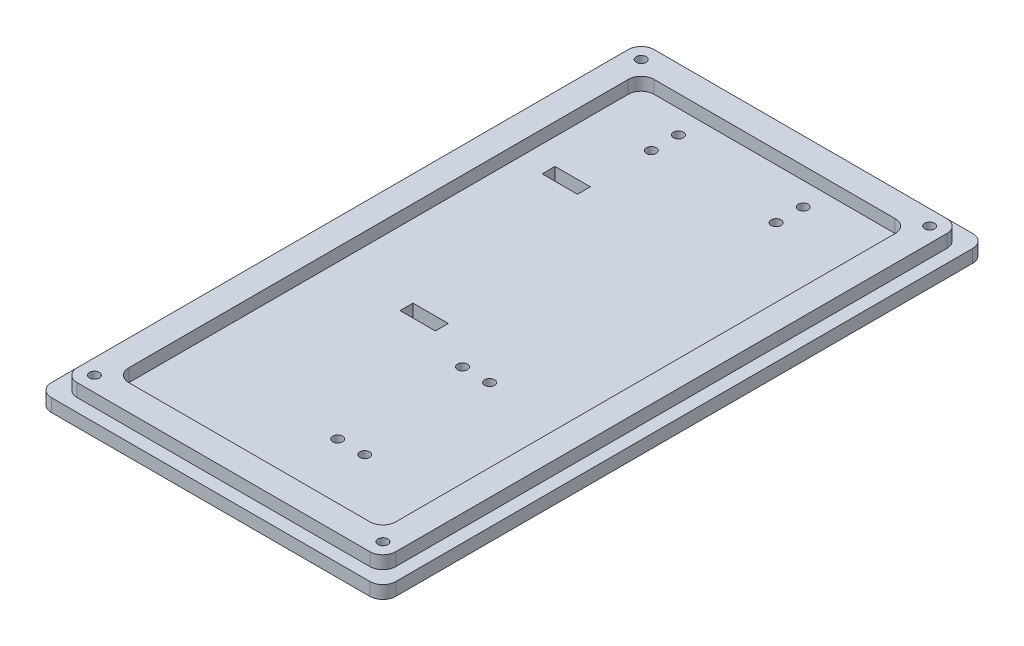
SolidWorks part; units mm, degrees
material "ABS"
ref_plane "Front Plane" through (0, 0, 0) normal (0, 0, 1) x (1, 0, 0)
ref_plane "Top Plane" through (0, 0, 0) normal (0, 1, 0) x (1, 0, 0)
ref_plane "Right Plane" through (0, 0, 0) normal (1, 0, 0) x (0, 0, -1)
sketch "Sketch1" plane through (0, 0, 0) normal (0, 1, 0) x (1, 0, 0)
  line L1 (3, 0) -> (77, 0)
  line L2 (0, 3) -> (0, 137)
  line L3 (3, 140) -> (77, 140)
  line L4 (80, 3) -> (80, 137)
  arc A0 (77, 0) -> (80, 3) centre (77, 3) ccw
  arc A1 (3, 0) -> (0, 3) centre (3, 3) cw
  arc A2 (77, 140) -> (80, 137) centre (77, 137) cw
  arc A3 (0, 137) -> (3, 140) centre (3, 137) cw
  point P9 (0, 0)
  point P12 (80, 140)
  point P15 (0, 140)
  dimension "D3" = 3
  dimension "D1" = 80
  dimension "D2" = 140
extrude "Boss-Extrude1" add sketch "Sketch1" along normal blind 3
sketch "Sketch2" plane through (0, 3, 0) normal (0, 1, 0) x (1, 0, 0)
  line L0 (0, 137) -> (0, 3) construction
  line L1 (6, 137) -> (74, 137)
  line L2 (3, 134) -> (3, 6)
  line L3 (6, 3) -> (74, 3)
  line L4 (77, 134) -> (77, 6)
  line L5 (77, 140) -> (3, 140) construction
  line L6 (80, 3) -> (80, 137) construction
  line L7 (3, 0) -> (77, 0) construction
  line L9 (12, 131) -> (68, 131)
  line L10 (9, 128) -> (9, 12)
  line L11 (12, 9) -> (68, 9)
  line L12 (71, 128) -> (71, 12)
  arc A0 (74, 137) -> (77, 134) centre (74, 134) cw
  arc A1 (74, 3) -> (77, 6) centre (74, 6) ccw
  arc A2 (3, 6) -> (6, 3) centre (6, 6) ccw
  arc A3 (6, 137) -> (3, 134) centre (6, 134) ccw
  arc A4 (9, 12) -> (12, 9) centre (12, 12) ccw
  arc A5 (68, 9) -> (71, 12) centre (68, 12) ccw
  arc A6 (68, 131) -> (71, 128) centre (68, 128) cw
  arc A7 (12, 131) -> (9, 128) centre (12, 128) ccw
  dimension "D9" = 3
  dimension "D10" = 3
  dimension "D1" = 3
  dimension "D2" = 3
  dimension "D3" = 3
  dimension "D4" = 3
  dimension "D5" = 6
  dimension "D6" = 6
  dimension "D7" = 6
  dimension "D8" = 6
extrude "Boss-Extrude2" add sketch "Sketch2" along normal blind 3
sketch "Sketch3" plane through (0, 6, 0) normal (0, 1, 0) x (1, 0, 0)
  line L0 (3, 0) -> (77, 0) construction
  line L1 (0, 137) -> (0, 3) construction
  line L2 (80, 3) -> (80, 137) construction
  line L3 (77, 140) -> (3, 140) construction
  circle A0 centre (6.5, 133.5) radius 1.15
  circle A1 centre (73.5, 133.5) radius 1.15
  circle A2 centre (73.5, 6.5) radius 1.15
  circle A3 centre (6.5, 6.5) radius 1.15
  dimension "D1" = 2.3
  dimension "D2" = 2.3
  dimension "D3" = 2.3
  dimension "D4" = 2.3
  dimension "D5" = 6.5
  dimension "D6" = 6.5
  dimension "D7" = 6.5
  dimension "D8" = 6.5
  dimension "D9" = 6.5
  dimension "D10" = 6.5
  dimension "D11" = 6.5
  dimension "D12" = 6.5
extrude "Cut-Extrude1" cut sketch "Sketch3" against normal through all
sketch "Sketch4" plane through (0, 0, 0) normal (0, -1, 0) x (1, 0, 0)
  line L0 (0, -137) -> (0, -3) construction
  line L1 (26, -58) -> (34.2, -58)
  line L2 (26, -58) -> (26, -61)
  line L3 (26, -61) -> (34.2, -61)
  line L4 (34.2, -58) -> (34.2, -61)
  line L5 (15, -102) -> (23.2, -102)
  line L6 (15, -102) -> (15, -105)
  line L7 (15, -105) -> (23.2, -105)
  line L8 (23.2, -102) -> (23.2, -105)
  line L9 (77, -140) -> (3, -140) construction
  line L10 (3, 0) -> (77, 0) construction
  dimension "D1" = 8.2
  dimension "D2" = 3
  dimension "D3" = 8.2
  dimension "D4" = 3
  dimension "D5" = 15
  dimension "D6" = 35
  dimension "D7" = 26
  dimension "D8" = 58
extrude "Cut-Extrude2" cut sketch "Sketch4" against normal blind 10
sketch "Sketch5" plane through (0, 0, 0) normal (0, -1, 0) x (1, 0, 0)
  line L0 (77, -140) -> (3, -140) construction
  line L1 (0, -137) -> (0, -3) construction
  circle A0 centre (23, -125.65) radius 1.15
  circle A1 centre (52, -125.65) radius 1.15
  circle A2 centre (52, -119.35) radius 1.15
  circle A3 centre (23, -119.35) radius 1.15
  dimension "D1" = 2.3
  dimension "D2" = 2.3
  dimension "D3" = 2.3
  dimension "D4" = 2.3
  dimension "D5" = 14.35
  dimension "D6" = 14.35
  dimension "D7" = 29
  dimension "D8" = 29
  dimension "D9" = 23
  dimension "D10" = 23
  dimension "D11" = 6.3
  dimension "D12" = 6.3
extrude "Cut-Extrude3" cut sketch "Sketch5" against normal blind 3
sketch "Sketch6" plane through (0, 0, 0) normal (0, -1, 0) x (1, 0, 0)
  line L0 (80, -3) -> (80, -137) construction
  line L1 (3, 0) -> (77, 0) construction
  circle A0 centre (50.88, -53.92) radius 1.15
  circle A1 centre (44.58, -53.92) radius 1.15
  circle A2 centre (50.88, -24.92) radius 1.15
  circle A3 centre (44.58, -24.92) radius 1.15
  point P12 (50.88, -36.3208)
  point P13 (42.0376, -37.5465)
  point P14 (50.88, -40.1026)
  dimension "D1" = 2.3
  dimension "D2" = 2.3
  dimension "D3" = 2.3
  dimension "D4" = 2.3
  dimension "D5" = 29.12
  dimension "D6" = 29.12
  dimension "D7" = 24.92
  dimension "D8" = 24.92
  dimension "D9" = 29
  dimension "D10" = 29
  dimension "D11" = 6.3
  dimension "D12" = 6.3
extrude "Cut-Extrude4" cut sketch "Sketch6" against normal blind 3
